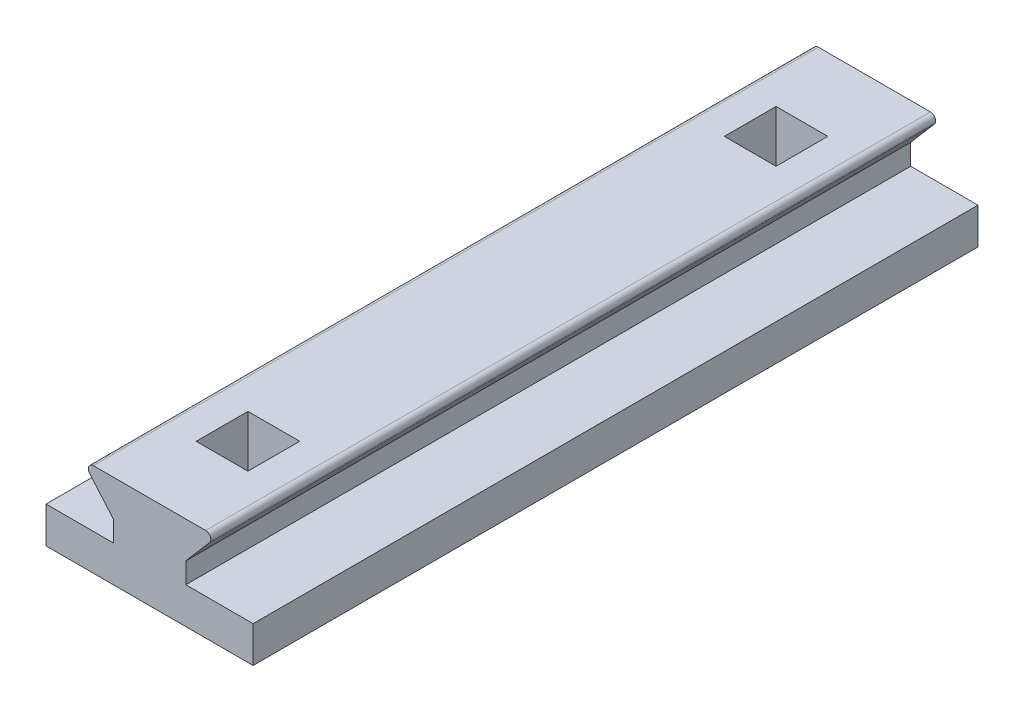
SolidWorks part; units mm, degrees
ref_plane "Front Plane" through (0, 0, 0) normal (0, 0, 1) x (1, 0, 0)
ref_plane "Top Plane" through (0, 0, 0) normal (0, 1, 0) x (1, 0, 0)
ref_plane "Right Plane" through (0, 0, 0) normal (1, 0, 0) x (0, 0, -1)
sketch "Sketch1" plane through (0, 0, 0) normal (0, 0, 1) x (1, 0, 0)
  line L0 (0, 0) -> (20, 0)
  line L1 (20, 0) -> (20, 3.5)
  line L2 (20, 3.5) -> (13.5, 3.5)
  line L3 (13.5, 3.5) -> (13.5, 5.5)
  line L6 (16.5, 9) -> (3.5, 9)
  line L9 (6.5, 5.5) -> (6.5, 3.5)
  line L10 (6.5, 3.5) -> (0, 3.5)
  line L11 (0, 3.5) -> (0, 0)
  line L12 (3.5, 9) -> (6.5, 5.5)
  line L13 (16.5, 9) -> (13.5, 5.5)
  dimension "D1" = 20
  dimension "D2" = 3.5
  dimension "D3" = 3.5
  dimension "D4" = 6.5
  dimension "D5" = 6.5
  dimension "D6" = 2
  dimension "D7" = 2
  dimension "D8" = 5.5
  dimension "D9" = 3
  dimension "D10" = 3
extrude "Boss-Extrude1" add sketch "Sketch1" along normal blind 70
fillet "Fillet3" radius 0.5 1 edges at (16.5, 9, 35)
fillet "Fillet4" radius 0.5 1 edges at (3.5, 9, 35)
sketch "Sketch2" plane through (0, 9, 0) normal (0, 1, 0) x (1, 0, 0)
  line L0 (15.4129, -70) -> (4.5871, -70) construction
  line L1 (12.5, -12) -> (7.5, -12)
  line L2 (12.5, -12) -> (12.5, -7)
  line L3 (12.5, -7) -> (7.5, -7)
  line L4 (7.5, -12) -> (7.5, -7)
  line L5 (12.5, -63) -> (7.5, -63)
  line L6 (12.5, -63) -> (12.5, -58)
  line L7 (12.5, -58) -> (7.5, -58)
  line L8 (7.5, -63) -> (7.5, -58)
  line L11 (20, -70) -> (20, 0) construction
  line L12 (15.4129, 0) -> (4.5871, 0) construction
  dimension "D1" = 5
  dimension "D2" = 5
  dimension "D3" = 7
  dimension "D4" = 7.5
  dimension "D5" = 5
  dimension "D6" = 5
  dimension "D7" = 7
  dimension "D8" = 7.5
extrude "Cut-Extrude1" cut sketch "Sketch2" against normal blind 5
sketch "Sketch3" plane through (0, 4, 0) normal (0, 1, 0) x (1, 0, 0)
  line L0 (7.5, -12) -> (12.5, -12) construction
  line L1 (7.5, -7) -> (7.5, -12) construction
  line L2 (12.5, -58) -> (7.5, -58) construction
  line L3 (7.5, -58) -> (7.5, -63) construction
  circle A0 centre (10, -9.5) radius 2
  circle A1 centre (10, -60.5) radius 2
  dimension "D1" = 4
  dimension "D2" = 4
  dimension "D3" = 2.5
  dimension "D4" = 2.5
  dimension "D5" = 2.5
  dimension "D6" = 2.5
extrude "Cut-Extrude2" cut sketch "Sketch3" against normal through all
